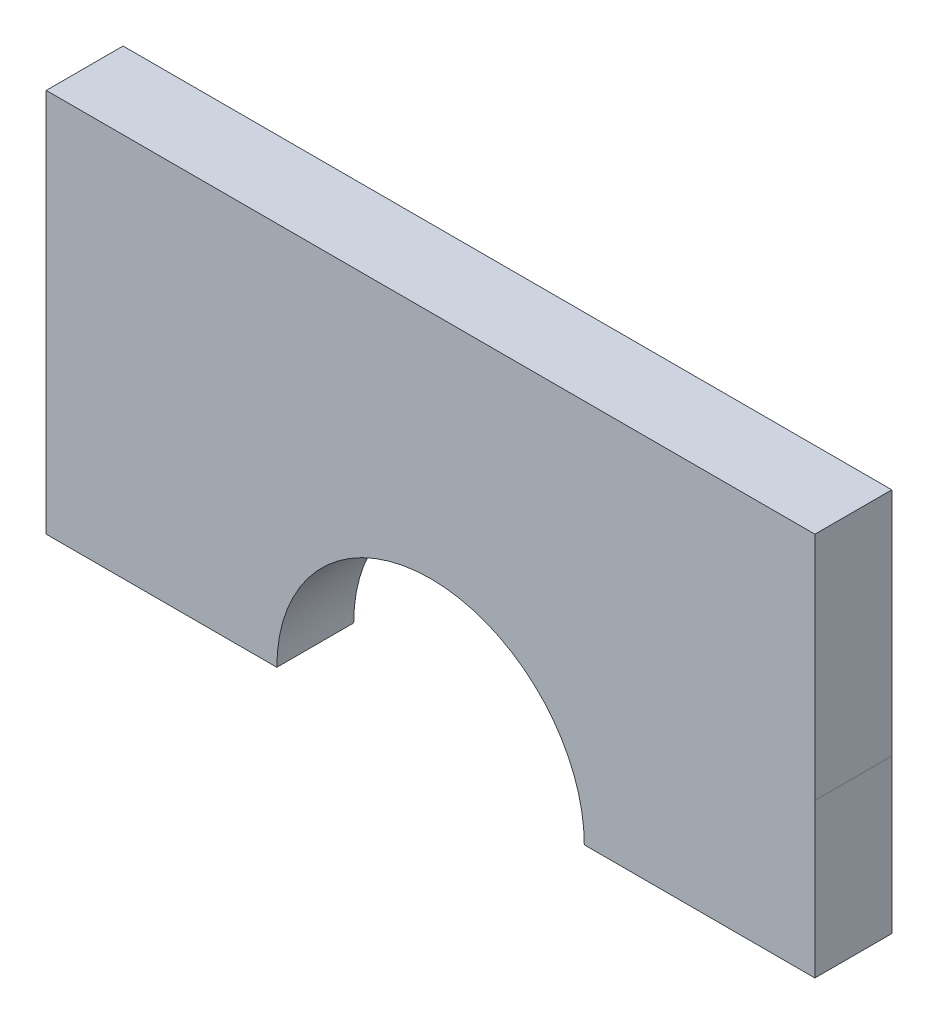
SolidWorks part; units mm, degrees
ref_plane "Front Plane" through (0, 0, 0) normal (0, 0, 1) x (1, 0, 0)
ref_plane "Top Plane" through (0, 0, 0) normal (0, 1, 0) x (1, 0, 0)
ref_plane "Right Plane" through (0, 0, 0) normal (1, 0, 0) x (0, 0, -1)
sketch "Sketch1" plane through (0, 0, 0) normal (0, 0, 1) x (1, 0, 0)
  line L1 (0, 0) -> (100, 0)
  line L2 (0, 0) -> (0, 50)
  line L3 (0, 50) -> (100, 50)
  line L4 (100, 0) -> (100, 50)
  dimension "D1" = 100
  dimension "D2" = 50
extrude "Boss-Extrude1" add sketch "Sketch1" along normal blind 10
sketch "Sketch2" plane through (0, 0, 0) normal (-1, 0, 0) x (0, 0, 1)
  line L0 (0, 20) -> (10, 20)
  line L1 (0, 50) -> (0, 0) construction
  line L2 (10, 50) -> (10, 0) construction
  line L3 (10, 0) -> (0, 0) construction
  dimension "D1" = 20
sketch "Sketch3" plane through (0, 0, 10) normal (0, 0, 1) x (1, 0, 0)
  line L0 (0, 0) -> (100, 0) construction
  circle A0 centre (50, 0) radius 20
  dimension "D1" = 40
extrude "Cut-Extrude1" cut sketch "Sketch3" against normal through all
split line "Split Line1"
sketch "Sketch4" plane through (100, 0, 0) normal (1, 0, 0) x (0, 0, -1)
  line L0 (-10, 20) -> (0, 20)
split line "Split Line2"
